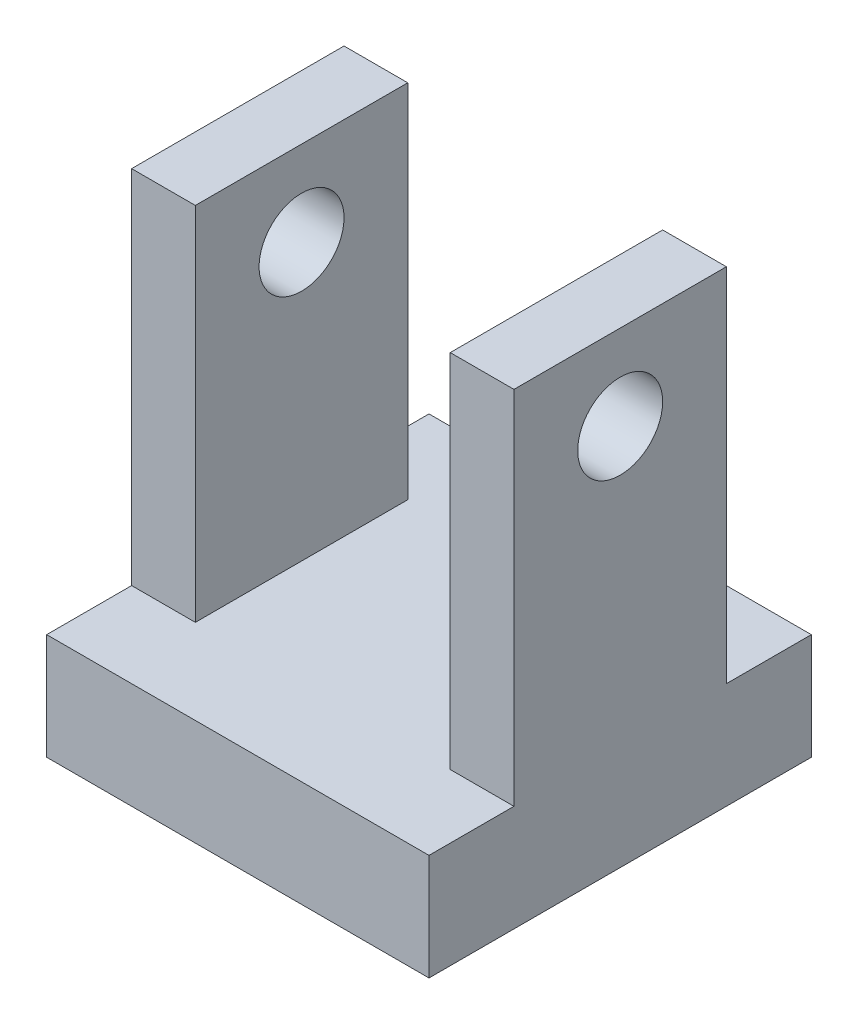
SolidWorks part; units mm, degrees
material "AISI 304"
ref_plane "Front Plane" through (0, 0, 0) normal (0, 0, 1) x (1, 0, 0)
ref_plane "Top Plane" through (0, 0, 0) normal (0, 1, 0) x (1, 0, 0)
ref_plane "Right Plane" through (0, 0, 0) normal (1, 0, 0) x (0, 0, -1)
sketch "Croquis1" plane through (0, 0, 0) normal (1, 0, 0) x (0, 0, -1)
  line L0 (45, 0) -> (-45, 0)
  line L1 (-45, 0) -> (-45, 25)
  line L2 (-45, 25) -> (-25, 25)
  line L3 (-25, 25) -> (-25, 110)
  line L4 (-25, 110) -> (25, 110)
  line L5 (25, 110) -> (25, 25)
  line L6 (25, 25) -> (45, 25)
  line L7 (45, 25) -> (45, 0)
  point P4 (0, 0)
  dimension "D1" = 25
  dimension "D2" = 90
  dimension "D3" = 50
  dimension "D4" = 110
  dimension "D5" = 25
  dimension "D6" = 20
extrude "Saliente-Extruir1" add sketch "Croquis1" along normal mid plane 90
sketch "Croquis2" plane through (0, 0, 25) normal (0, 0, 1) x (1, 0, 0)
  line L0 (30, 25) -> (-30, 25)
  line L1 (45, 25) -> (-45, 25) construction
  line L2 (-30, 25) -> (-30, 110)
  line L3 (45, 110) -> (-45, 110) construction
  line L4 (-30, 110) -> (0, 110)
  line L5 (0, 110) -> (30, 110)
  line L6 (30, 110) -> (30, 25)
  point P5 (0, 25)
  dimension "D1" = 30
  dimension "D2" = 30
extrude "Cortar-Extruir1" cut sketch "Croquis2" against normal blind 90
sketch "Croquis3" plane through (45, 0, 0) normal (1, 0, 0) x (0, 0, -1)
  line L0 (0, 0) -> (0, 90) construction
  circle A0 centre (0, 90) radius 10
  dimension "D2" = 20
  dimension "D1" = 90
extrude "Cortar-Extruir2" cut sketch "Croquis3" against normal through all
